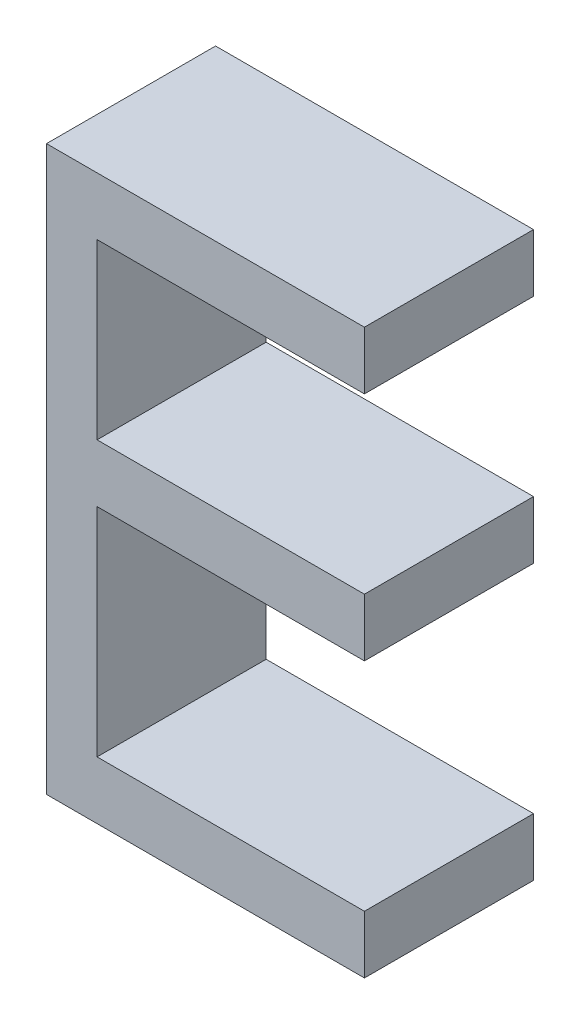
SolidWorks part; units mm, degrees
ref_plane "Plan de face" through (0, 0, 0) normal (0, 0, 1) x (1, 0, 0)
ref_plane "Plan de dessus" through (0, 0, 0) normal (0, 1, 0) x (1, 0, 0)
ref_plane "Plan de droite" through (0, 0, 0) normal (1, 0, 0) x (0, 0, -1)
sketch "Esquisse1" plane through (0, 0, 0) normal (0, 0, 1) x (1, 0, 0)
  text T0 "E" font "Century Gothic" height 5
extrude "Boss.-Extru.1" add sketch "Esquisse1" along normal blind 1.5
